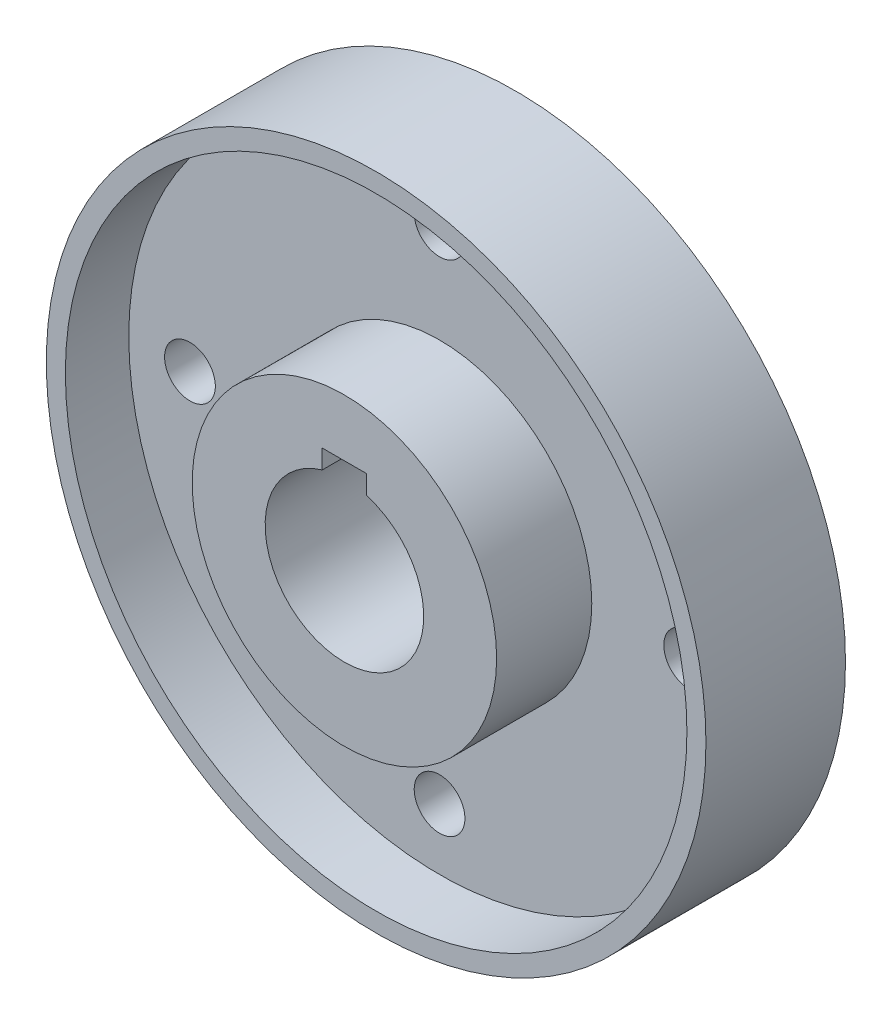
SolidWorks part; units mm, degrees
ref_plane "Front Plane" through (0, 0, 0) normal (0, 0, 1) x (1, 0, 0)
ref_plane "Top Plane" through (0, 0, 0) normal (0, 1, 0) x (1, 0, 0)
ref_plane "Right Plane" through (0, 0, 0) normal (1, 0, 0) x (0, 0, -1)
sketch "Sketch1" plane through (0, 0, 0) normal (1, 0, 0) x (0, 0, -1)
  line L0 (-44, 104) -> (0, 104)
  line L1 (0, 55) -> (0, -55) construction
  line L2 (0, 104) -> (0, 48)
  line L3 (0, 48) -> (-5, 48)
  line L4 (-5, 48) -> (-5, 25)
  line L5 (-5, 25) -> (-54, 25)
  line L6 (-54, 25) -> (-54, 48)
  line L7 (-54, 48) -> (-24, 48)
  line L8 (-24, 48) -> (-24, 98)
  line L9 (-24, 98) -> (-44, 98)
  line L10 (-44, 98) -> (-44, 104)
  line L11 (55, 0) -> (-55, 0) construction
  line L12 (-52.4965, 0) -> (46.7439, 0) construction
  dimension "D1" = 6
  dimension "D2" = 20
  dimension "D3" = 5
  dimension "D4" = 30
  dimension "D5" = 48
  dimension "D6" = 25
  dimension "D7" = 48
  dimension "D8" = 50
  dimension "D9" = 44
revolve "Revolve1" add sketch "Sketch1" angle 360 about L12
sketch "Sketch2" plane through (0, 0, 0) normal (0, 0, 1) x (1, 0, 0)
  line L0 (0, -55.4092) -> (0, 55.4092) construction
  line L1 (-7, 30) -> (7, 30)
  line L2 (-7, 30) -> (-7, 20)
  line L3 (-7, 20) -> (7, 20)
  line L4 (7, 30) -> (7, 20)
  line L5 (-7, 30) -> (7, 20) construction
  line L6 (-7, 20) -> (7, 30) construction
  circle A0 centre (0, 0) radius 25 construction
  point P0 (0, 25)
  dimension "D1" = 14
  dimension "D2" = 10
extrude "Cut-Extrude1" cut sketch "Sketch2" along normal blind 146
sketch "Sketch3" plane through (0, 0, 0) normal (0, 0, 1) x (1, 0, 0)
  line L0 (0, -29.7) -> (0, 29.7) construction
  circle A0 centre (0, 78.7044) radius 8
extrude "Cut-Extrude2" cut sketch "Sketch3" along normal blind 217
pattern_circular "CirPattern1" count 4 over 360 about axis through (0, 0, 0) along (0, 0, 1) of "Cut-Extrude2"
